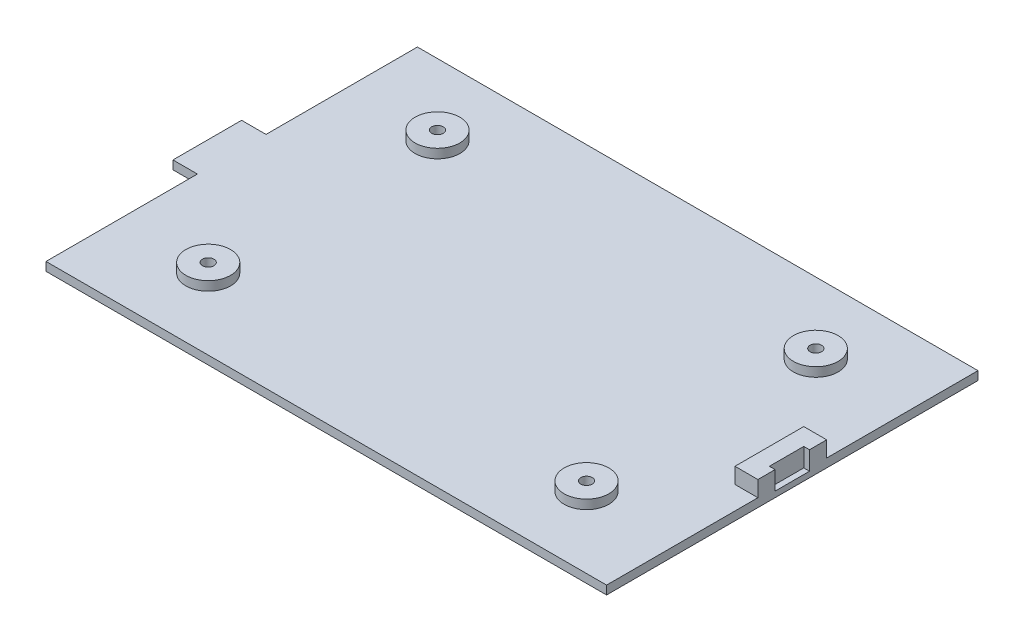
SolidWorks part; units mm, degrees
material "PLA"
ref_plane "前视基准面" through (0, 0, 0) normal (0, 0, 1) x (1, 0, 0)
ref_plane "上视基准面" through (0, 0, 0) normal (0, 1, 0) x (1, 0, 0)
ref_plane "右视基准面" through (0, 0, 0) normal (1, 0, 0) x (0, 0, -1)
other "Configuration Table"
sketch "草图1" plane through (0, 0, 0) normal (0, 1, 0) x (1, 0, 0)
  line L0 (-51.7144, -10.061) -> (-55.9767, -10.061)
  line L1 (-51.7144, 16.3517) -> (46.0856, 16.3517)
  line L2 (-51.7144, 16.3517) -> (-51.7144, -10.061)
  line L3 (-51.7144, -48.4483) -> (46.0856, -48.4483)
  line L4 (46.0856, 16.3517) -> (46.0856, -48.4483)
  line L5 (-51.7144, 16.3517) -> (46.0856, -48.4483) construction
  line L6 (-51.7144, -48.4483) -> (46.0856, 16.3517) construction
  line L7 (-55.9767, -10.061) -> (-55.9767, -22.0356)
  line L8 (-51.8144, -9.961) -> (-51.8144, 16.4517) construction
  line L9 (46.1856, -48.5483) -> (-51.8144, -48.5483) construction
  line L10 (-55.9767, -22.0356) -> (-51.7144, -22.0356)
  line L11 (-51.7144, -22.0356) -> (-51.7144, -48.4483)
  line L12 (-51.8144, -9.961) -> (-56.0767, -9.961) construction
  line L13 (-56.0767, -22.1356) -> (-51.8144, -22.1356) construction
  line L14 (-56.0767, -9.961) -> (-56.0767, -22.1356) construction
  point P0 (0, 0)
  dimension "D1" = 97.8
  dimension "D2" = 64.8
  dimension "D3" = 0.1
  dimension "D4" = 0.1
  dimension "D5" = 0.1
  dimension "D6" = 0.1
  dimension "D7" = 0.1
extrude "凸台-拉伸1" add sketch "草图1" along normal blind 1.5
sketch "草图2" plane through (0, 0, 0) normal (0, -1, 0) x (1, 0, 0)
  line L1 (43.1856, 16.0483) -> (26.5724, 16.0483) construction
  line L4 (43.1856, 41.0483) -> (43.1856, -8.9517) construction
  circle A1 centre (-35.8144, 36.0483) radius 5
  circle A4 centre (30.1856, -3.9517) radius 4 construction
  circle A6 centre (30.1856, -3.9517) radius 5
  circle A7 centre (-35.8144, -3.9517) radius 5
  circle A11 centre (30.1856, 36.0483) radius 5
  circle A12 centre (-35.8144, -3.9517) radius 4 construction
  circle A13 centre (-35.8144, 36.0483) radius 4 construction
  dimension "D1" = 10
  dimension "D2" = 10
  dimension "D3" = 10
extrude "防滑切除-拉伸1" cut sketch "草图2" against normal blind 0.5
sketch "草图14" plane through (0, 0, 0) normal (0, -1, 0) x (1, 0, 0)
  line L1 (45.0856, 13.0483) -> (45.0856, 19.0483)
  line L2 (45.0856, 19.0483) -> (46.0856, 19.0483)
  line L3 (46.0856, 19.0483) -> (46.0856, 22.0483)
  line L4 (46.0856, 48.4483) -> (46.0856, -16.3517) construction
  line L5 (46.0856, 22.0483) -> (42.0856, 22.0483)
  line L6 (42.0856, 22.0483) -> (42.0856, 10.0483)
  line L7 (42.0856, 10.0483) -> (46.0856, 10.0483)
  line L8 (46.0856, 10.0483) -> (46.0856, 13.0483)
  line L9 (46.0856, 13.0483) -> (45.0856, 13.0483)
  line L10 (46.0856, 16.0483) -> (41.9652, 16.0483) construction
  line L11 (46.1856, 18.9483) -> (45.1856, 18.9483) construction
  line L12 (45.1856, 18.9483) -> (45.1856, 13.5483) construction
  dimension "D1" = 0.1
  dimension "D2" = 0.1
  dimension "D3" = 3
  dimension "D4" = 3
  dimension "D5" = 3
extrude "LED限位凸台-拉伸3" add sketch "草图14" along normal up to surface (4.25 mm away) from surface
sketch "草图15" plane through (0, 0, 0) normal (0, -1, 0) x (1, 0, 0)
  line L1 (43.1856, 16.0483) -> (11.4258, 16.0483) construction
  line L2 (43.1856, 41.0483) -> (43.1856, -8.9517) construction
  circle A1 centre (-35.8144, 36.0483) radius 2
  circle A3 centre (30.1856, 36.0483) radius 2
  circle A4 centre (30.1856, 36.0483) radius 4 construction
  circle A7 centre (-35.8144, 36.0483) radius 5 construction
  circle A9 centre (30.1856, -3.9517) radius 2
  circle A10 centre (-35.8144, -3.9517) radius 2
  dimension "D2" = 4
  dimension "D4" = 4
extrude "螺丝孔位切除-拉伸2" cut sketch "草图15" against normal up to next
sketch "草图16" plane through (0, 0, 0) normal (0, -1, 0) x (1, 0, 0)
  line L0 (46.0856, 16.0483) -> (25.3615, 16.0483) construction
  line L2 (46.0856, 48.4483) -> (46.0856, -16.3517) construction
  circle A1 centre (30.1856, 36.0483) radius 1
  circle A3 centre (-35.8144, 36.0483) radius 1
  circle A9 centre (-35.8144, 36.0483) radius 3.9
  circle A10 centre (30.1856, 36.0483) radius 2 construction
  circle A13 centre (30.1856, 36.0483) radius 3.9
  circle A30 centre (30.1856, -3.9517) radius 3.9
  circle A31 centre (-35.8144, -3.9517) radius 3.9
  circle A32 centre (-35.8144, -3.9517) radius 1
  circle A33 centre (30.1856, -3.9517) radius 1
  dimension "D4" = 2
  dimension "D5" = 7.8
  dimension "D2" = 7.8
  dimension "D1" = 2
extrude "螺丝孔凸台-拉伸4" add sketch "草图16" along normal up to surface (1.6 mm away) from surface
sketch "草图17" plane through (0, 0, 0) normal (0, -1, 0) x (1, 0, 0)
  line L0 (45.0856, 13.0483) -> (46.1856, 13.0483) construction
  line L1 (45.0856, 19.0483) -> (45.0856, 13.0483) construction
  line L2 (46.1856, 19.0483) -> (45.0856, 19.0483) construction
  line L3 (45.0856, 13.0483) -> (46.0856, 13.0483)
  line L4 (45.0856, 19.0483) -> (45.0856, 13.0483)
  line L5 (46.0856, 19.0483) -> (45.0856, 19.0483)
  line L6 (46.0856, 13.0483) -> (46.0856, 19.0483)
  line L7 (46.0856, 48.4483) -> (46.0856, -16.3517) construction
extrude "LED灯嵌入切除-拉伸2" cut sketch "草图17" along normal blind 0.5 from surface at -1.5 starting at face at (-35.8144, 1.5, -0.0517)
